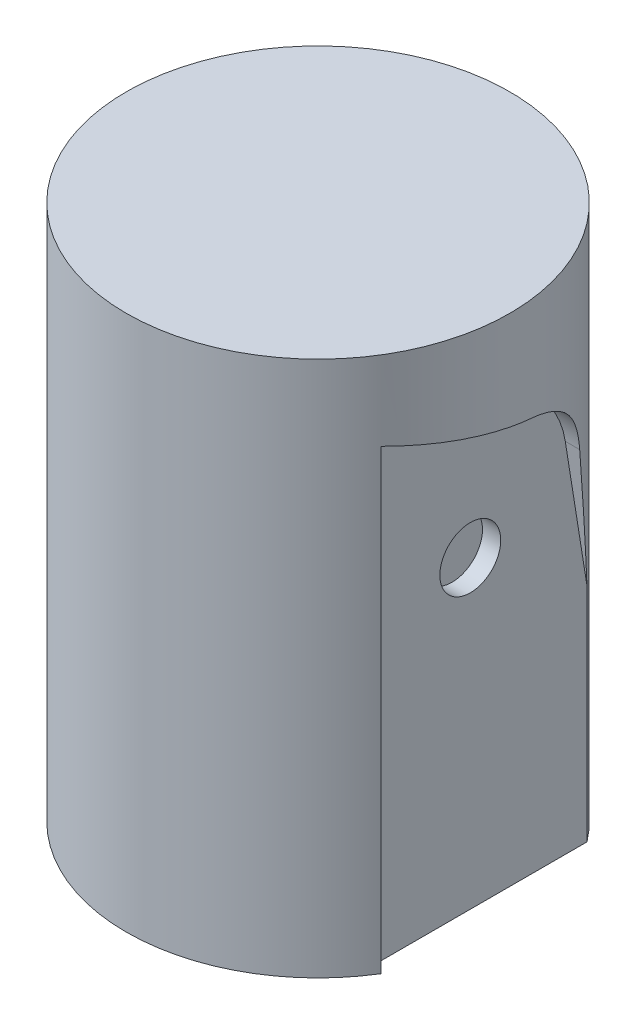
SolidWorks part; units mm, degrees
ref_plane "前视基准面" through (0, 0, 0) normal (0, 0, 1) x (1, 0, 0)
ref_plane "上视基准面" through (0, 0, 0) normal (0, 1, 0) x (1, 0, 0)
ref_plane "右视基准面" through (0, 0, 0) normal (1, 0, 0) x (0, 0, -1)
sketch "草图1" plane through (0, 0, 0) normal (0, 1, 0) x (1, 0, 0)
  circle A0 centre (0, 0) radius 31.5
  dimension "D1" = 63
extrude "凸台-拉伸1" add sketch "草图1" along normal blind 88
ref_plane "基准面1" through (31.5, 0, 0) normal (1, 0, 0) x (0, 0, -1)
sketch "草图2" plane through (31.5, 0, 0) normal (1, 0, 0) x (0, 0, -1)
  line L0 (-31.5, 88) -> (-16.5, 88) construction
  line L1 (31.5, 88) -> (-31.5, 88) construction
  line L2 (-16.5, 88) -> (-16.5, 75) construction
  line L3 (-16.5, 75) -> (3.6253, 71.1149)
  line L4 (15.5944, 58.7524) -> (24.9773, 0)
  line L5 (-31.5, 0) -> (31.5, 0) construction
  line L6 (24.9773, 0) -> (-16.5, 0)
  line L7 (-16.5, 0) -> (-16.5, 75)
  arc A0 (3.6253, 71.1149) -> (15.5944, 58.7524) centre (0.7821, 56.3868) cw
  point P13 (13.938, 69.124)
  dimension "D6" = 15
  dimension "D1" = 15
  dimension "D2" = 13
  dimension "D3" = 110
  dimension "D4" = 31
  dimension "D5" = 70
extrude "切除-拉伸1" cut sketch "草图2" against normal blind 6.5
mirror "镜向1" about plane through (0, 0, 0) normal (1, 0, 0) of "切除-拉伸1"
sketch "草图3" plane through (25, 0, 0) normal (1, 0, 0) x (0, 0, -1)
  line L0 (31.5, 0) -> (31.5, 88) construction
  line L1 (-16.5, 0) -> (19.1638, 0) construction
  circle A0 centre (0, 50) radius 5
  dimension "D1" = 10
  dimension "D2" = 31.5
  dimension "D3" = 50
extrude "切除-拉伸2" cut sketch "草图3" against normal blind 3
mirror "镜向2" about plane through (0, 0, 0) normal (1, 0, 0) of "切除-拉伸2"
